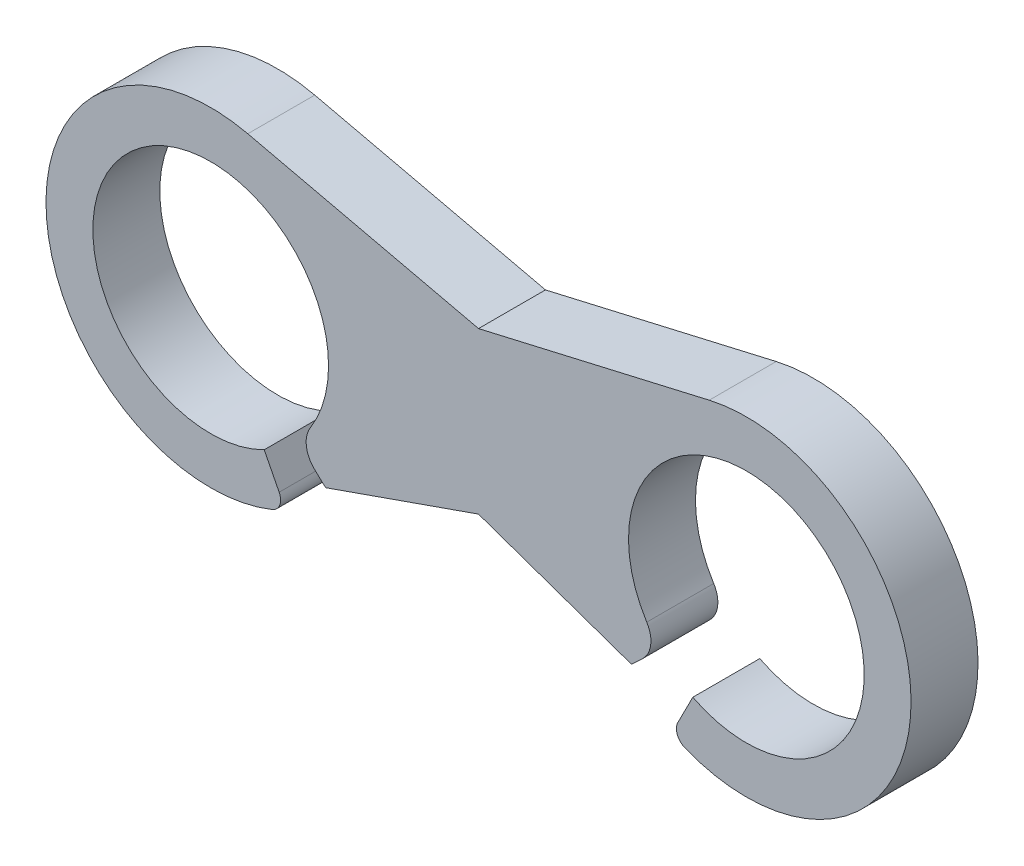
SolidWorks part; units mm, degrees
ref_plane "Front Plane" through (0, 0, 0) normal (0, 0, 1) x (1, 0, 0)
ref_plane "Top Plane" through (0, 0, 0) normal (0, 1, 0) x (1, 0, 0)
ref_plane "Right Plane" through (0, 0, 0) normal (1, 0, 0) x (0, 0, -1)
sketch "Sketch1" plane through (0, 0, 0) normal (0, 0, 1) x (1, 0, 0)
  line L0 (0, 0) -> (0, 13.9566) construction
  line L1 (0, 4) -> (8.6145, 5.9919)
  line L2 (5.7084, -4) -> (0, -2)
  line L3 (10, 0) -> (5.7084, -4) construction
  line L4 (5.7084, -4) -> (6.7527, -4.6856) construction
  line L5 (10, 0) -> (7.2066, -5.479) construction
  line L6 (5.7084, -4) -> (6.7813, -3)
  line L7 (7.2066, -5.479) -> (8.0015, -3.9199)
  line L8 (0, 4) -> (0, -2)
  arc A0 (8.0015, -3.9199) -> (6.7813, -3) centre (10, 0) ccw
  arc A1 (7.2066, -5.479) -> (8.6145, 5.9919) centre (10, 0) ccw
  point P1 (0, 0)
  dimension "D2" = 12.3
  dimension "D3" = 8.8
  dimension "D1" = 10
  dimension "D4" = 4
  dimension "D5" = 6
  dimension "D6" = 20
  dimension "D7" = 2
  dimension "D8" = 3
extrude "Boss-Extrude1" add sketch "Sketch1" along normal blind 2.5
mirror "Mirror1" about plane through (0, 4, 2.5) normal (1, 0, 0) of "Boss-Extrude1"
fillet "Fillet1" radius 0.5 2 edges at (-7.2066, -5.479, 1.25) (7.2066, -5.479, 1.25)
fillet "Fillet2" radius 1 2 edges at (-6.7813, -3, 1.25) (6.7813, -3, 1.25)
